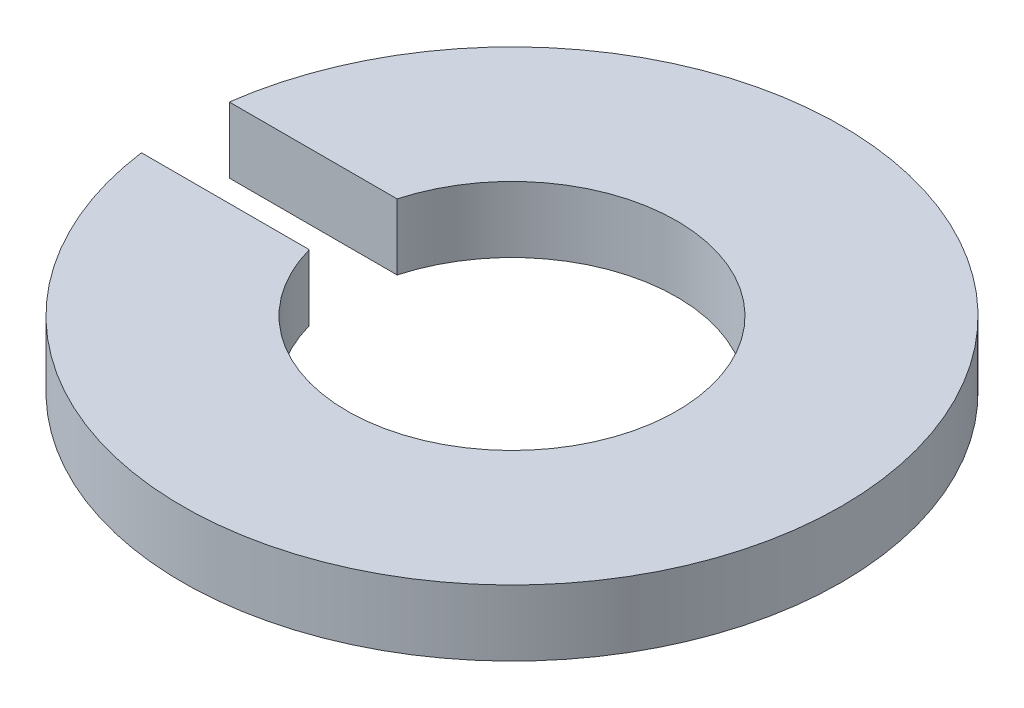
SolidWorks part; units mm, degrees
ref_plane "Front Plane" through (0, 0, 0) normal (0, 0, 1) x (1, 0, 0)
ref_plane "Top Plane" through (0, 0, 0) normal (0, 1, 0) x (1, 0, 0)
ref_plane "Right Plane" through (0, 0, 0) normal (1, 0, 0) x (0, 0, -1)
sketch "Sketch2" plane through (0, 0, 0) normal (0, 1, 0) x (1, 0, 0)
  circle A0 centre (0, 0) radius 1.5
  circle A1 centre (0, 0) radius 0.75
  dimension "D1" = 3
  dimension "D2" = 1.5
extrude "Boss-Extrude1" add sketch "Sketch2" along normal blind 0.3
sketch "Sketch3" plane through (0, 0.3, 0) normal (0, 1, 0) x (1, 0, 0)
  line L1 (-0.6983, 0.2) -> (-1.8859, 0.2)
  line L2 (-0.6983, 0.2) -> (-0.6983, -0.2)
  line L3 (-0.6983, -0.2) -> (-1.8859, -0.2)
  line L4 (-1.8859, 0.2) -> (-1.8859, -0.2)
  dimension "D1" = 0.2
  dimension "D2" = 0.2
extrude "Cut-Extrude1" cut sketch "Sketch3" against normal blind 0.3
